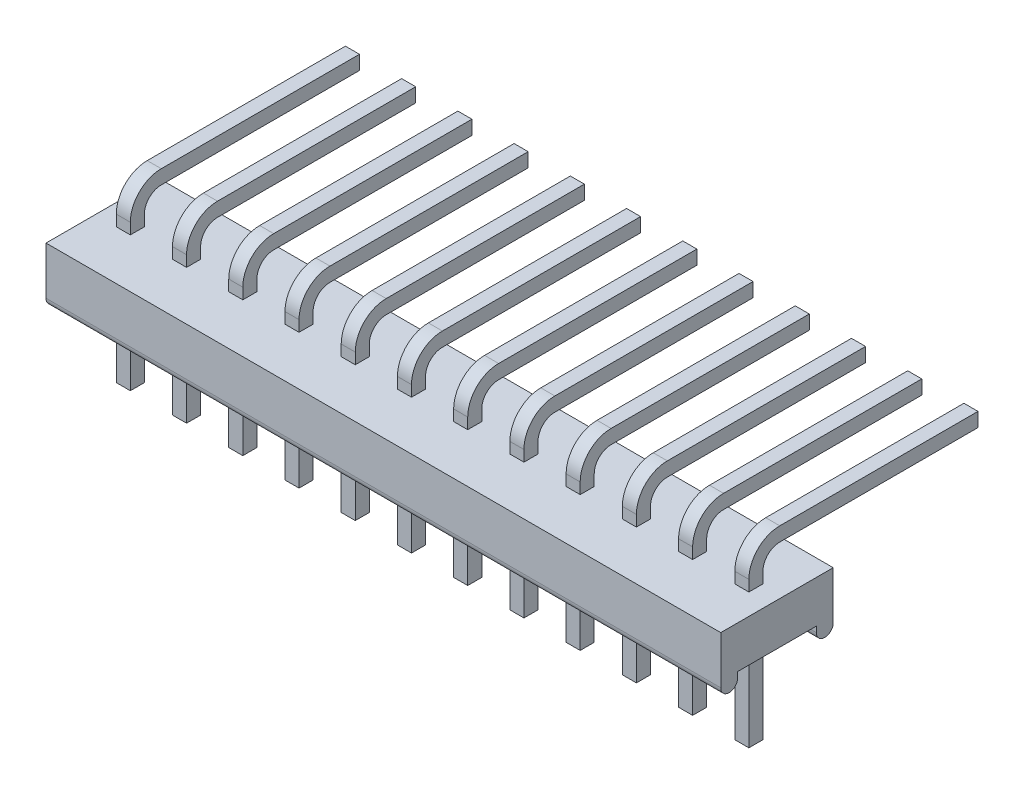
SolidWorks part; units mm, degrees
ref_plane "Alzado" through (0, 0, 0) normal (0, 0, 1) x (1, 0, 0)
ref_plane "Planta" through (0, 0, 0) normal (0, 1, 0) x (1, 0, 0)
ref_plane "Vista lateral" through (0, 0, 0) normal (1, 0, 0) x (0, 0, -1)
ref_plane "Plano1" through (15.24, 0, 0) normal (1, 0, 0) x (0, 0, -1)
sketch "Croquis1" plane through (15.24, 0, 0) normal (1, 0, 0) x (0, 0, -1)
  line L0 (-2.54, 1.905) -> (-2.54, -0.254)
  line L1 (-1.778, -0.254) -> (-1.778, 0)
  line L2 (-1.778, 0) -> (1.778, 0)
  line L3 (1.778, 0) -> (1.778, -0.254)
  line L4 (2.54, -0.254) -> (2.54, 1.905)
  line L5 (2.54, 1.905) -> (-2.54, 1.905)
  arc A0 (-2.54, -0.254) -> (-1.778, -0.254) centre (-2.159, -0.254) ccw
  arc A1 (1.778, -0.254) -> (2.54, -0.254) centre (2.159, -0.254) ccw
extrude "Saliente-Extruir1" add sketch "Croquis1" against normal blind 30.48
sketch "Croquis2" plane through (0, 1.905, 0) normal (0, 1, 0) x (-1, 0, 0)
  line L0 (-14.2875, 0.3175) -> (-13.6525, 0.3175)
  line L1 (-13.6525, 0.3175) -> (-13.6525, -0.3175)
  line L2 (-13.6525, -0.3175) -> (-14.2875, -0.3175)
  line L3 (-14.2875, -0.3175) -> (-14.2875, 0.3175)
extrude "Saliente-Extruir2" add sketch "Croquis2" along normal blind 1.8923
sketch "Croquis3" plane through (0, 0, -0.3175) normal (0, 0, -1) x (-1, 0, 0)
  line L0 (-13.6525, 3.1623) -> (-14.2875, 3.1623)
  line L1 (-14.2875, 3.1623) -> (-14.2875, 3.7973)
  line L2 (-14.2875, 3.7973) -> (-13.6525, 3.7973)
  line L3 (-13.6525, 3.7973) -> (-13.6525, 3.1623)
extrude "Saliente-Extruir3" add sketch "Croquis3" along normal blind 9.7155
sketch "Croquis4" plane through (0, 1.905, 0) normal (0, 1, 0) x (-1, 0, 0)
  line L0 (-11.7475, 0.3175) -> (-11.1125, 0.3175)
  line L1 (-11.1125, 0.3175) -> (-11.1125, -0.3175)
  line L2 (-11.1125, -0.3175) -> (-11.7475, -0.3175)
  line L3 (-11.7475, -0.3175) -> (-11.7475, 0.3175)
extrude "Saliente-Extruir4" add sketch "Croquis4" along normal blind 1.8923
sketch "Croquis5" plane through (0, 0, -0.3175) normal (0, 0, -1) x (-1, 0, 0)
  line L0 (-11.1125, 3.1623) -> (-11.7475, 3.1623)
  line L1 (-11.7475, 3.1623) -> (-11.7475, 3.7973)
  line L2 (-11.7475, 3.7973) -> (-11.1125, 3.7973)
  line L3 (-11.1125, 3.7973) -> (-11.1125, 3.1623)
extrude "Saliente-Extruir5" add sketch "Croquis5" along normal blind 9.7155
sketch "Croquis6" plane through (0, 1.905, 0) normal (0, 1, 0) x (-1, 0, 0)
  line L0 (-9.2075, 0.3175) -> (-8.5725, 0.3175)
  line L1 (-8.5725, 0.3175) -> (-8.5725, -0.3175)
  line L2 (-8.5725, -0.3175) -> (-9.2075, -0.3175)
  line L3 (-9.2075, -0.3175) -> (-9.2075, 0.3175)
extrude "Saliente-Extruir6" add sketch "Croquis6" along normal blind 1.8923
sketch "Croquis7" plane through (0, 0, -0.3175) normal (0, 0, -1) x (-1, 0, 0)
  line L0 (-8.5725, 3.1623) -> (-9.2075, 3.1623)
  line L1 (-9.2075, 3.1623) -> (-9.2075, 3.7973)
  line L2 (-9.2075, 3.7973) -> (-8.5725, 3.7973)
  line L3 (-8.5725, 3.7973) -> (-8.5725, 3.1623)
extrude "Saliente-Extruir7" add sketch "Croquis7" along normal blind 9.7155
sketch "Croquis8" plane through (0, 1.905, 0) normal (0, 1, 0) x (-1, 0, 0)
  line L0 (-6.6675, 0.3175) -> (-6.0325, 0.3175)
  line L1 (-6.0325, 0.3175) -> (-6.0325, -0.3175)
  line L2 (-6.0325, -0.3175) -> (-6.6675, -0.3175)
  line L3 (-6.6675, -0.3175) -> (-6.6675, 0.3175)
extrude "Saliente-Extruir8" add sketch "Croquis8" along normal blind 1.8923
sketch "Croquis9" plane through (0, 0, -0.3175) normal (0, 0, -1) x (-1, 0, 0)
  line L0 (-6.0325, 3.1623) -> (-6.6675, 3.1623)
  line L1 (-6.6675, 3.1623) -> (-6.6675, 3.7973)
  line L2 (-6.6675, 3.7973) -> (-6.0325, 3.7973)
  line L3 (-6.0325, 3.7973) -> (-6.0325, 3.1623)
extrude "Saliente-Extruir9" add sketch "Croquis9" along normal blind 9.7155
sketch "Croquis10" plane through (0, 1.905, 0) normal (0, 1, 0) x (-1, 0, 0)
  line L0 (-4.1275, 0.3175) -> (-3.4925, 0.3175)
  line L1 (-3.4925, 0.3175) -> (-3.4925, -0.3175)
  line L2 (-3.4925, -0.3175) -> (-4.1275, -0.3175)
  line L3 (-4.1275, -0.3175) -> (-4.1275, 0.3175)
extrude "Saliente-Extruir10" add sketch "Croquis10" along normal blind 1.8923
sketch "Croquis11" plane through (0, 0, -0.3175) normal (0, 0, -1) x (-1, 0, 0)
  line L0 (-3.4925, 3.1623) -> (-4.1275, 3.1623)
  line L1 (-4.1275, 3.1623) -> (-4.1275, 3.7973)
  line L2 (-4.1275, 3.7973) -> (-3.4925, 3.7973)
  line L3 (-3.4925, 3.7973) -> (-3.4925, 3.1623)
extrude "Saliente-Extruir11" add sketch "Croquis11" along normal blind 9.7155
sketch "Croquis12" plane through (0, 1.905, 0) normal (0, 1, 0) x (-1, 0, 0)
  line L0 (-1.5875, 0.3175) -> (-0.9525, 0.3175)
  line L1 (-0.9525, 0.3175) -> (-0.9525, -0.3175)
  line L2 (-0.9525, -0.3175) -> (-1.5875, -0.3175)
  line L3 (-1.5875, -0.3175) -> (-1.5875, 0.3175)
extrude "Saliente-Extruir12" add sketch "Croquis12" along normal blind 1.8923
sketch "Croquis13" plane through (0, 0, -0.3175) normal (0, 0, -1) x (-1, 0, 0)
  line L0 (-0.9525, 3.1623) -> (-1.5875, 3.1623)
  line L1 (-1.5875, 3.1623) -> (-1.5875, 3.7973)
  line L2 (-1.5875, 3.7973) -> (-0.9525, 3.7973)
  line L3 (-0.9525, 3.7973) -> (-0.9525, 3.1623)
extrude "Saliente-Extruir13" add sketch "Croquis13" along normal blind 9.7155
sketch "Croquis14" plane through (0, 1.905, 0) normal (0, 1, 0) x (-1, 0, 0)
  line L0 (0.9525, 0.3175) -> (1.5875, 0.3175)
  line L1 (1.5875, 0.3175) -> (1.5875, -0.3175)
  line L2 (1.5875, -0.3175) -> (0.9525, -0.3175)
  line L3 (0.9525, -0.3175) -> (0.9525, 0.3175)
extrude "Saliente-Extruir14" add sketch "Croquis14" along normal blind 1.8923
sketch "Croquis15" plane through (0, 0, -0.3175) normal (0, 0, -1) x (-1, 0, 0)
  line L0 (1.5875, 3.1623) -> (0.9525, 3.1623)
  line L1 (0.9525, 3.1623) -> (0.9525, 3.7973)
  line L2 (0.9525, 3.7973) -> (1.5875, 3.7973)
  line L3 (1.5875, 3.7973) -> (1.5875, 3.1623)
extrude "Saliente-Extruir15" add sketch "Croquis15" along normal blind 9.7155
sketch "Croquis16" plane through (0, 1.905, 0) normal (0, 1, 0) x (-1, 0, 0)
  line L0 (3.4925, 0.3175) -> (4.1275, 0.3175)
  line L1 (4.1275, 0.3175) -> (4.1275, -0.3175)
  line L2 (4.1275, -0.3175) -> (3.4925, -0.3175)
  line L3 (3.4925, -0.3175) -> (3.4925, 0.3175)
extrude "Saliente-Extruir16" add sketch "Croquis16" along normal blind 1.8923
sketch "Croquis17" plane through (0, 0, -0.3175) normal (0, 0, -1) x (-1, 0, 0)
  line L0 (4.1275, 3.1623) -> (3.4925, 3.1623)
  line L1 (3.4925, 3.1623) -> (3.4925, 3.7973)
  line L2 (3.4925, 3.7973) -> (4.1275, 3.7973)
  line L3 (4.1275, 3.7973) -> (4.1275, 3.1623)
extrude "Saliente-Extruir17" add sketch "Croquis17" along normal blind 9.7155
sketch "Croquis18" plane through (0, 1.905, 0) normal (0, 1, 0) x (-1, 0, 0)
  line L0 (6.0325, 0.3175) -> (6.6675, 0.3175)
  line L1 (6.6675, 0.3175) -> (6.6675, -0.3175)
  line L2 (6.6675, -0.3175) -> (6.0325, -0.3175)
  line L3 (6.0325, -0.3175) -> (6.0325, 0.3175)
extrude "Saliente-Extruir18" add sketch "Croquis18" along normal blind 1.8923
sketch "Croquis19" plane through (0, 0, -0.3175) normal (0, 0, -1) x (-1, 0, 0)
  line L0 (6.6675, 3.1623) -> (6.0325, 3.1623)
  line L1 (6.0325, 3.1623) -> (6.0325, 3.7973)
  line L2 (6.0325, 3.7973) -> (6.6675, 3.7973)
  line L3 (6.6675, 3.7973) -> (6.6675, 3.1623)
extrude "Saliente-Extruir19" add sketch "Croquis19" along normal blind 9.7155
sketch "Croquis20" plane through (0, 1.905, 0) normal (0, 1, 0) x (-1, 0, 0)
  line L0 (8.5725, 0.3175) -> (9.2075, 0.3175)
  line L1 (9.2075, 0.3175) -> (9.2075, -0.3175)
  line L2 (9.2075, -0.3175) -> (8.5725, -0.3175)
  line L3 (8.5725, -0.3175) -> (8.5725, 0.3175)
extrude "Saliente-Extruir20" add sketch "Croquis20" along normal blind 1.8923
sketch "Croquis21" plane through (0, 0, -0.3175) normal (0, 0, -1) x (-1, 0, 0)
  line L0 (9.2075, 3.1623) -> (8.5725, 3.1623)
  line L1 (8.5725, 3.1623) -> (8.5725, 3.7973)
  line L2 (8.5725, 3.7973) -> (9.2075, 3.7973)
  line L3 (9.2075, 3.7973) -> (9.2075, 3.1623)
extrude "Saliente-Extruir21" add sketch "Croquis21" along normal blind 9.7155
sketch "Croquis22" plane through (0, 1.905, 0) normal (0, 1, 0) x (-1, 0, 0)
  line L0 (11.1125, 0.3175) -> (11.7475, 0.3175)
  line L1 (11.7475, 0.3175) -> (11.7475, -0.3175)
  line L2 (11.7475, -0.3175) -> (11.1125, -0.3175)
  line L3 (11.1125, -0.3175) -> (11.1125, 0.3175)
extrude "Saliente-Extruir22" add sketch "Croquis22" along normal blind 1.8923
sketch "Croquis23" plane through (0, 0, -0.3175) normal (0, 0, -1) x (-1, 0, 0)
  line L0 (11.7475, 3.1623) -> (11.1125, 3.1623)
  line L1 (11.1125, 3.1623) -> (11.1125, 3.7973)
  line L2 (11.1125, 3.7973) -> (11.7475, 3.7973)
  line L3 (11.7475, 3.7973) -> (11.7475, 3.1623)
extrude "Saliente-Extruir23" add sketch "Croquis23" along normal blind 9.7155
sketch "Croquis24" plane through (0, 1.905, 0) normal (0, 1, 0) x (-1, 0, 0)
  line L0 (13.6525, 0.3175) -> (14.2875, 0.3175)
  line L1 (14.2875, 0.3175) -> (14.2875, -0.3175)
  line L2 (14.2875, -0.3175) -> (13.6525, -0.3175)
  line L3 (13.6525, -0.3175) -> (13.6525, 0.3175)
extrude "Saliente-Extruir24" add sketch "Croquis24" along normal blind 1.8923
sketch "Croquis25" plane through (0, 0, -0.3175) normal (0, 0, -1) x (-1, 0, 0)
  line L0 (14.2875, 3.1623) -> (13.6525, 3.1623)
  line L1 (13.6525, 3.1623) -> (13.6525, 3.7973)
  line L2 (13.6525, 3.7973) -> (14.2875, 3.7973)
  line L3 (14.2875, 3.7973) -> (14.2875, 3.1623)
extrude "Saliente-Extruir25" add sketch "Croquis25" along normal blind 9.7155
sketch "Croquis26" plane through (0, 0, 0) normal (0, -1, 0) x (1, 0, 0)
  line L0 (14.2875, 0.3175) -> (14.2875, -0.3175)
  line L1 (14.2875, -0.3175) -> (13.6525, -0.3175)
  line L2 (13.6525, -0.3175) -> (13.6525, 0.3175)
  line L3 (13.6525, 0.3175) -> (14.2875, 0.3175)
extrude "Saliente-Extruir26" add sketch "Croquis26" along normal blind 4.191
sketch "Croquis27" plane through (0, 0, 0) normal (0, -1, 0) x (1, 0, 0)
  line L0 (11.7475, 0.3175) -> (11.7475, -0.3175)
  line L1 (11.7475, -0.3175) -> (11.1125, -0.3175)
  line L2 (11.1125, -0.3175) -> (11.1125, 0.3175)
  line L3 (11.1125, 0.3175) -> (11.7475, 0.3175)
extrude "Saliente-Extruir27" add sketch "Croquis27" along normal blind 4.191
sketch "Croquis28" plane through (0, 0, 0) normal (0, -1, 0) x (1, 0, 0)
  line L0 (9.2075, 0.3175) -> (9.2075, -0.3175)
  line L1 (9.2075, -0.3175) -> (8.5725, -0.3175)
  line L2 (8.5725, -0.3175) -> (8.5725, 0.3175)
  line L3 (8.5725, 0.3175) -> (9.2075, 0.3175)
extrude "Saliente-Extruir28" add sketch "Croquis28" along normal blind 4.191
sketch "Croquis29" plane through (0, 0, 0) normal (0, -1, 0) x (1, 0, 0)
  line L0 (6.6675, 0.3175) -> (6.6675, -0.3175)
  line L1 (6.6675, -0.3175) -> (6.0325, -0.3175)
  line L2 (6.0325, -0.3175) -> (6.0325, 0.3175)
  line L3 (6.0325, 0.3175) -> (6.6675, 0.3175)
extrude "Saliente-Extruir29" add sketch "Croquis29" along normal blind 4.191
sketch "Croquis30" plane through (0, 0, 0) normal (0, -1, 0) x (1, 0, 0)
  line L0 (4.1275, 0.3175) -> (4.1275, -0.3175)
  line L1 (4.1275, -0.3175) -> (3.4925, -0.3175)
  line L2 (3.4925, -0.3175) -> (3.4925, 0.3175)
  line L3 (3.4925, 0.3175) -> (4.1275, 0.3175)
extrude "Saliente-Extruir30" add sketch "Croquis30" along normal blind 4.191
sketch "Croquis31" plane through (0, 0, 0) normal (0, -1, 0) x (1, 0, 0)
  line L0 (1.5875, 0.3175) -> (1.5875, -0.3175)
  line L1 (1.5875, -0.3175) -> (0.9525, -0.3175)
  line L2 (0.9525, -0.3175) -> (0.9525, 0.3175)
  line L3 (0.9525, 0.3175) -> (1.5875, 0.3175)
extrude "Saliente-Extruir31" add sketch "Croquis31" along normal blind 4.191
sketch "Croquis32" plane through (0, 0, 0) normal (0, -1, 0) x (1, 0, 0)
  line L0 (-0.9525, 0.3175) -> (-0.9525, -0.3175)
  line L1 (-0.9525, -0.3175) -> (-1.5875, -0.3175)
  line L2 (-1.5875, -0.3175) -> (-1.5875, 0.3175)
  line L3 (-1.5875, 0.3175) -> (-0.9525, 0.3175)
extrude "Saliente-Extruir32" add sketch "Croquis32" along normal blind 4.191
sketch "Croquis33" plane through (0, 0, 0) normal (0, -1, 0) x (1, 0, 0)
  line L0 (-3.4925, 0.3175) -> (-3.4925, -0.3175)
  line L1 (-3.4925, -0.3175) -> (-4.1275, -0.3175)
  line L2 (-4.1275, -0.3175) -> (-4.1275, 0.3175)
  line L3 (-4.1275, 0.3175) -> (-3.4925, 0.3175)
extrude "Saliente-Extruir33" add sketch "Croquis33" along normal blind 4.191
sketch "Croquis34" plane through (0, 0, 0) normal (0, -1, 0) x (1, 0, 0)
  line L0 (-6.0325, 0.3175) -> (-6.0325, -0.3175)
  line L1 (-6.0325, -0.3175) -> (-6.6675, -0.3175)
  line L2 (-6.6675, -0.3175) -> (-6.6675, 0.3175)
  line L3 (-6.6675, 0.3175) -> (-6.0325, 0.3175)
extrude "Saliente-Extruir34" add sketch "Croquis34" along normal blind 4.191
sketch "Croquis35" plane through (0, 0, 0) normal (0, -1, 0) x (1, 0, 0)
  line L0 (-8.5725, 0.3175) -> (-8.5725, -0.3175)
  line L1 (-8.5725, -0.3175) -> (-9.2075, -0.3175)
  line L2 (-9.2075, -0.3175) -> (-9.2075, 0.3175)
  line L3 (-9.2075, 0.3175) -> (-8.5725, 0.3175)
extrude "Saliente-Extruir35" add sketch "Croquis35" along normal blind 4.191
sketch "Croquis36" plane through (0, 0, 0) normal (0, -1, 0) x (1, 0, 0)
  line L0 (-11.1125, 0.3175) -> (-11.1125, -0.3175)
  line L1 (-11.1125, -0.3175) -> (-11.7475, -0.3175)
  line L2 (-11.7475, -0.3175) -> (-11.7475, 0.3175)
  line L3 (-11.7475, 0.3175) -> (-11.1125, 0.3175)
extrude "Saliente-Extruir36" add sketch "Croquis36" along normal blind 4.191
sketch "Croquis37" plane through (0, 0, 0) normal (0, -1, 0) x (1, 0, 0)
  line L0 (-13.6525, 0.3175) -> (-13.6525, -0.3175)
  line L1 (-13.6525, -0.3175) -> (-14.2875, -0.3175)
  line L2 (-14.2875, -0.3175) -> (-14.2875, 0.3175)
  line L3 (-14.2875, 0.3175) -> (-13.6525, 0.3175)
extrude "Saliente-Extruir37" add sketch "Croquis37" along normal blind 4.191
fillet "Redondeo1" radius 0.762 12 edges at (11.43, 3.1623, -0.3175) (13.97, 3.1623, -0.3175) (1.27, 3.1623, -0.3175) (6.35, 3.1623, -0.3175) (-8.89, 3.1623, -0.3175) (-3.81, 3.1623, -0.3175) (-11.43, 3.1623, -0.3175) (8.89, 3.1623, -0.3175) (-13.97, 3.1623, -0.3175) (-6.35, 3.1623, -0.3175) (-1.27, 3.1623, -0.3175) (3.81, 3.1623, -0.3175)
fillet "Redondeo2" radius 1.397 12 edges at (-3.81, 3.7973, 0.3175) (-13.97, 3.7973, 0.3175) (-8.89, 3.7973, 0.3175) (13.97, 3.7973, 0.3175) (-1.27, 3.7973, 0.3175) (11.43, 3.7973, 0.3175) (-6.35, 3.7973, 0.3175) (8.89, 3.7973, 0.3175) (-11.43, 3.7973, 0.3175) (6.35, 3.7973, 0.3175) (3.81, 3.7973, 0.3175) (1.27, 3.7973, 0.3175)
